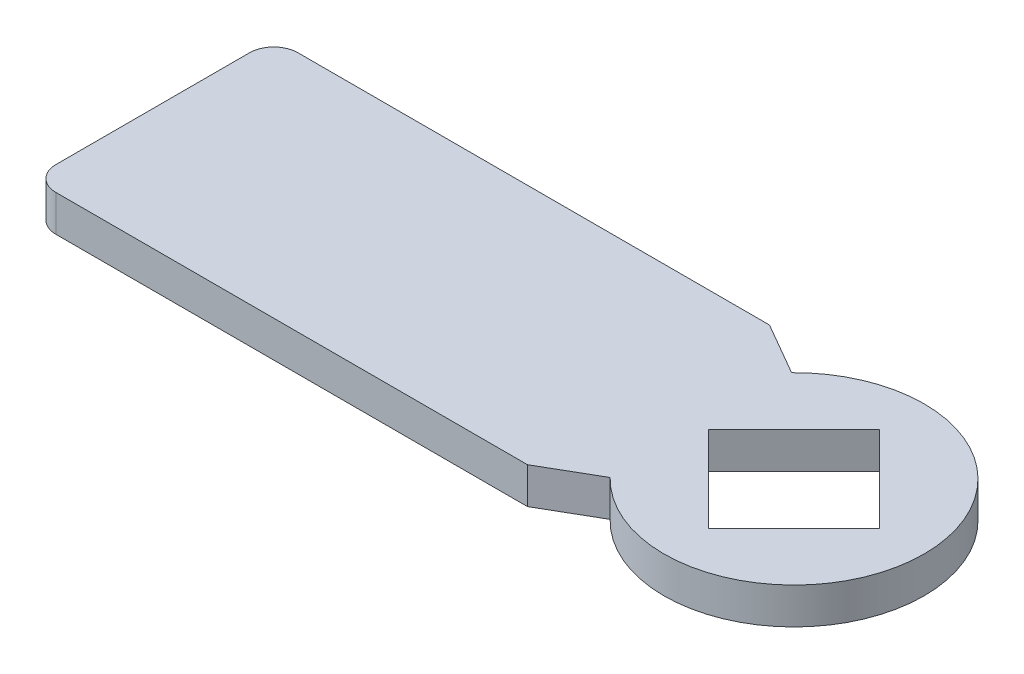
SolidWorks part; units mm, degrees
ref_plane "前视基准面" through (0, 0, 0) normal (0, 0, 1) x (1, 0, 0)
ref_plane "上视基准面" through (0, 0, 0) normal (0, 1, 0) x (1, 0, 0)
ref_plane "右视基准面" through (0, 0, 0) normal (1, 0, 0) x (0, 0, -1)
sketch "草图2" plane through (0, 0, 0) normal (0, 1, 0) x (1, 0, 0)
  line L0 (-12.0316, -10) -> (-7.7015, -7.5)
  line L1 (-53, 10) -> (-12.0316, 10)
  line L2 (-53, 10) -> (-53, -10)
  line L3 (-53, -10) -> (-12.0316, -10)
  line L4 (-59.6233, 0) -> (20.4513, 0) construction
  line L5 (-12.0316, 10) -> (-7.7015, 7.5)
  arc A0 (-7.7015, -7.5) -> (-7.7015, 7.5) centre (0, 0) ccw
  dimension "D3" = 30
  dimension "D4" = 21.5
  dimension "D5" = 5
  dimension "D1" = 53
  dimension "D2" = 20
extrude "凸台-拉伸1" add sketch "草图2" along normal blind 3
fillet "圆角1" radius 2 2 edges at (-53, 1.5, -10) (-53, 1.5, 10)
sketch "草图3" plane through (0, 3, 0) normal (0, 1, 0) x (1, 0, 0)
  line L0 (0, 0) -> (0, 13.5966) construction
  line L1 (0, 7.0711) -> (-7.0711, 0)
  line L2 (-7.0711, 0) -> (0, -7.0711)
  line L3 (0, -7.0711) -> (7.0711, 0)
  line L4 (7.0711, 0) -> (0, 7.0711)
  circle A0 centre (0, 0) radius 5 construction
  dimension "D1" = 10
extrude "切除-拉伸1" cut sketch "草图3" against normal through all
